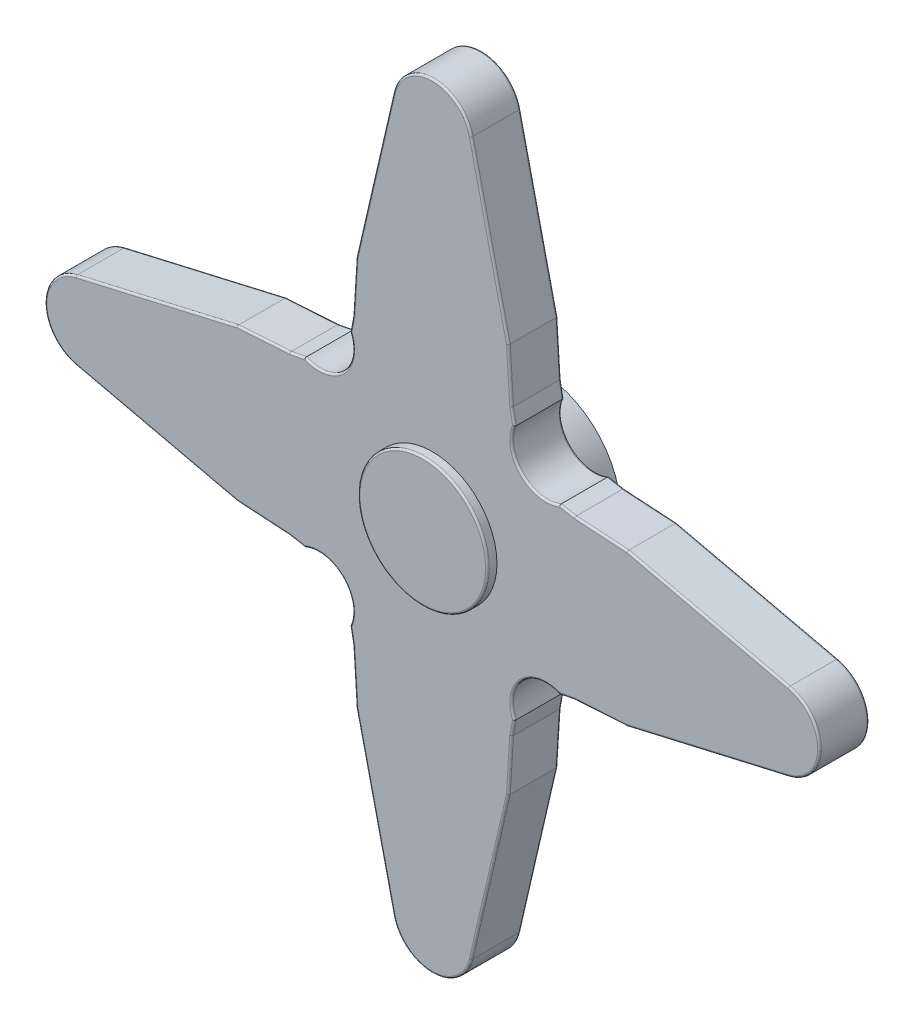
SolidWorks part; units mm, degrees
ref_plane "Front Plane" through (0, 0, 0) normal (0, 0, 1) x (1, 0, 0)
ref_plane "Top Plane" through (0, 0, 0) normal (0, 1, 0) x (1, 0, 0)
ref_plane "Right Plane" through (0, 0, 0) normal (1, 0, 0) x (0, 0, -1)
sketch "Sketch1" plane through (0, 0, 0) normal (0, 0, 1) x (1, 0, 0)
  line L0 (10.25, 4) -> (18.7219, 2.0463)
  line L1 (10.25, 4) -> (7.4875, 4.1728)
  line L2 (6.6928, 4.3231) -> (7.4875, 4.1728)
  line L7 (6.6928, -4.3231) -> (7.4875, -4.1728)
  line L8 (10.25, -4) -> (7.4875, -4.1728)
  line L9 (10.25, -4) -> (18.7219, -2.0463)
  line L10 (4.3231, 6.6928) -> (4.1728, 7.4875)
  line L11 (-4.3231, 6.6928) -> (-4.1728, 7.4875)
  line L12 (6.6928, -4.3231) -> (7.4875, -4.1728)
  line L13 (6.6928, 4.3231) -> (7.4875, 4.1728)
  line L14 (-4.3231, -6.6928) -> (-4.1728, -7.4875)
  line L15 (4.3231, -6.6928) -> (4.1728, -7.4875)
  line L16 (4, -10.25) -> (2.0463, -18.7219)
  line L17 (-20.35, 0) -> (-20.35, 4) construction
  line L18 (-20.35, 4) -> (-10.25, 4) construction
  line L19 (-10.25, 4) -> (-18.7219, 2.0463)
  line L22 (-10.25, 4) -> (-7.4875, 4.1728)
  line L23 (-10.25, -4) -> (-7.4875, -4.1728)
  line L24 (-10.25, -4) -> (-18.7219, -2.0463)
  line L25 (4, 10.25) -> (2.0463, 18.7219)
  line L26 (4, 10.25) -> (4.1728, 7.4875)
  line L27 (4, -10.25) -> (4.1728, -7.4875)
  line L28 (-4, 10.25) -> (-2.0463, 18.7219)
  line L29 (-4, 10.25) -> (-4.1728, 7.4875)
  line L30 (4.3231, -6.6928) -> (4.1728, -7.4875)
  line L31 (10.25, -4) -> (18.7219, -2.0463)
  line L32 (10.25, -4) -> (7.4875, -4.1728)
  line L33 (-4.3231, -6.6928) -> (-4.1728, -7.4875)
  line L34 (10.25, 4) -> (18.7219, 2.0463)
  line L35 (10.25, 4) -> (7.4875, 4.1728)
  line L36 (-4, -10.25) -> (-4.1728, -7.4875)
  line L37 (-4, -10.25) -> (-2.0463, -18.7219)
  line L38 (-4, -10.25) -> (-4.1728, -7.4875)
  line L39 (-4, -10.25) -> (-2.0463, -18.7219)
  line L40 (4, -10.25) -> (2.0463, -18.7219)
  line L41 (4, -10.25) -> (4.1728, -7.4875)
  line L42 (-10.25, -4) -> (-18.7219, -2.0463)
  line L49 (-10.25, -4) -> (-7.4875, -4.1728)
  line L50 (-6.6928, -4.3231) -> (-7.4875, -4.1728)
  line L51 (-6.6928, 4.3231) -> (-7.4875, 4.1728)
  line L52 (-10.25, 4) -> (-7.4875, 4.1728)
  line L53 (-10.25, 4) -> (-18.7219, 2.0463)
  arc A0 (-18.7219, 2.0463) -> (-18.6403, -2.0634) centre (-18.25, 0) ccw
  arc A1 (2.0634, 18.6403) -> (-2.0634, 18.6403) centre (0, 18.25) ccw
  arc A2 (18.7219, -2.0463) -> (18.7219, 2.0463) centre (18.25, 0) ccw
  arc A3 (-2.0463, -18.7219) -> (2.0463, -18.7219) centre (0, -18.25) ccw
  arc A4 (-5.9728, 4.1728) -> (-4.3231, 6.6928) centre (-5.9728, 5.9728) ccw
  arc A9 (-5.9728, -4.1728) -> (-4.3231, -6.6928) centre (-5.9728, -5.9728) cw
  arc A10 (4.1728, 5.9728) -> (6.6928, 4.3231) centre (5.9728, 5.9728) ccw
  arc A11 (-4.1728, 5.9728) -> (-5.9728, 4.1728) centre (-5.9728, 5.9728) cw
  arc A12 (5.9728, -4.1728) -> (4.3231, -6.6928) centre (5.9728, -5.9728) ccw
  arc A13 (5.9728, 4.1728) -> (4.3231, 6.6928) centre (5.9728, 5.9728) cw
  arc A14 (-4.1728, -5.9728) -> (-5.9728, -4.1728) centre (-5.9728, -5.9728) ccw
  arc A15 (4.1728, -5.9728) -> (6.6928, -4.3231) centre (5.9728, -5.9728) cw
  arc A16 (4.1728, 5.9728) -> (6.6928, 4.3231) centre (5.9728, 5.9728) ccw
  arc A17 (4.1728, -5.9728) -> (6.6928, -4.3231) centre (5.9728, -5.9728) cw
  arc A18 (5.9728, -4.1728) -> (4.3231, -6.6928) centre (5.9728, -5.9728) ccw
  arc A19 (-5.9728, -4.1728) -> (-4.3231, -6.6928) centre (-5.9728, -5.9728) cw
  arc A20 (-4.1728, -5.9728) -> (-6.6928, -4.3231) centre (-5.9728, -5.9728) ccw
  arc A21 (-4.1728, 5.9728) -> (-6.6928, 4.3231) centre (-5.9728, 5.9728) cw
  dimension "D2" = 4.2
  dimension "D4" = 4
  dimension "D9" = 4
  dimension "D10" = 10.1
  dimension "D3" = 4
  dimension "D7" = 4
extrude "Boss-Extrude2" add sketch "Sketch1" along normal blind 2.6
fillet "Fillet1" radius 0.1 64 edges at (0, 20.35, 0) (-3.0231, 14.4859, 0) (-4.0864, 8.8687, 0) (-4.2479, 7.0902, 0) (-4.7, 4.7, 0) (-7.0902, 4.2479, 0) (-8.8687, 4.0864, 0) (-14.4859, 3.0231, 0) (-20.35, 0, 0) (-14.4859, -3.0231, 0) (-8.8687, -4.0864, 0) (-7.0902, -4.2479, 0) (-4.7, -4.7, 0) (-4.2479, -7.0902, 0) (-4.0864, -8.8687, 0) (-3.0231, -14.4859, 0) (0, -20.35, 0) (3.0231, -14.4859, 0) (4.0864, -8.8687, 0) (4.2479, -7.0902, 0) (4.7, -4.7, 0) (7.0902, -4.2479, 0) (8.8687, -4.0864, 0) (14.4859, -3.0231, 0) (20.35, 0, 0) (14.4859, 3.0231, 0) (8.8687, 4.0864, 0) (7.0902, 4.2479, 0) (4.7, 4.7, 0) (4.2479, 7.0902, 0) (4.0864, 8.8687, 0) (3.0231, 14.4859, 0) (4.0864, 8.8687, 2.6) (4.2479, 7.0902, 2.6) (4.7, 4.7, 2.6) (7.0902, 4.2479, 2.6) (8.8687, 4.0864, 2.6) (14.4859, 3.0231, 2.6) (20.35, 0, 2.6) (14.4859, -3.0231, 2.6) (8.8687, -4.0864, 2.6) (7.0902, -4.2479, 2.6) (4.7, -4.7, 2.6) (4.2479, -7.0902, 2.6) (4.0864, -8.8687, 2.6) (3.0231, -14.4859, 2.6) (0, -20.35, 2.6) (-3.0231, -14.4859, 2.6) (-4.0864, -8.8687, 2.6) (-4.2479, -7.0902, 2.6) (-4.7, -4.7, 2.6) (-7.0902, -4.2479, 2.6) (-8.8687, -4.0864, 2.6) (-14.4859, -3.0231, 2.6) (-20.35, 0, 2.6) (-14.4859, 3.0231, 2.6) (-8.8687, 4.0864, 2.6) (-7.0902, 4.2479, 2.6) (-4.7, 4.7, 2.6) (-4.2479, 7.0902, 2.6) (-4.0864, 8.8687, 2.6) (-3.0231, 14.4859, 2.6) (0, 20.35, 2.6) (3.0231, 14.4859, 2.6)
sketch "Sketch2" plane through (0, 0, 2.6) normal (0, 0, 1) x (1, 0, 0)
  circle A0 centre (0, 0) radius 3.4
  point P3 (0, 0)
  dimension "D1" = 6.8
extrude "Boss-Extrude3" add sketch "Sketch2" along normal blind 0.5
fillet "Fillet2" radius 0.1 1 edges at (3.4, 0, 3.1)
sketch "Sketch3" plane through (0, 0, 0) normal (0, 0, -1) x (-1, 0, 0)
  circle A0 centre (0, 0) radius 2.85
  circle A1 centre (0, 0) radius 4.3
  dimension "D1" = 5.7
  dimension "D2" = 8.6
extrude "Boss-Extrude4" add sketch "Sketch3" along normal blind 3
